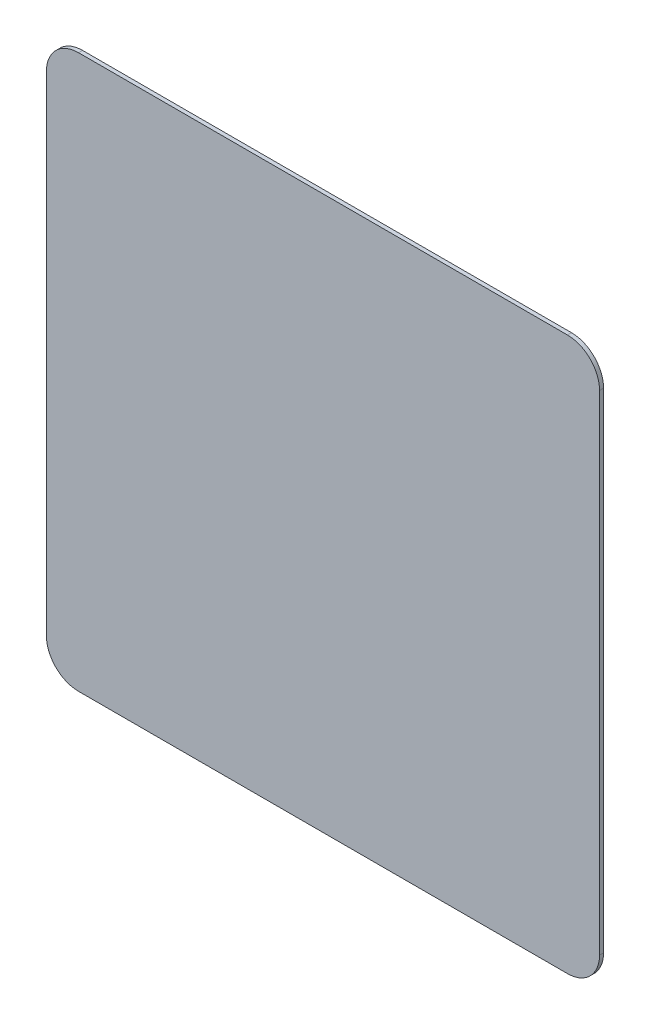
SolidWorks part; units mm, degrees
ref_plane "Front Plane" through (0, 0, 0) normal (0, 0, 1) x (1, 0, 0)
ref_plane "Top Plane" through (0, 0, 0) normal (0, 1, 0) x (1, 0, 0)
ref_plane "Right Plane" through (0, 0, 0) normal (1, 0, 0) x (0, 0, -1)
sketch "Sketch1" plane through (0, 0, 0) normal (0, 0, 1) x (1, 0, 0)
  line L1 (0, 0) -> (219.075, 0)
  line L2 (0, 0) -> (0, -219.075)
  line L3 (0, -219.075) -> (219.075, -219.075)
  line L4 (219.075, 0) -> (219.075, -219.075)
  dimension "D1" = 219.075
  dimension "D2" = 219.075
extrude "Boss-Extrude1" add sketch "Sketch1" along normal blind 1.5875
fillet "Fillet13" radius 12.7 2 edges at (219.075, -219.075, 0.7937) (219.075, 0, 0.7937)
fillet "Fillet14" radius 12.7 2 edges at (0, -219.075, 0.7937) (0, 0, 0.7937)
